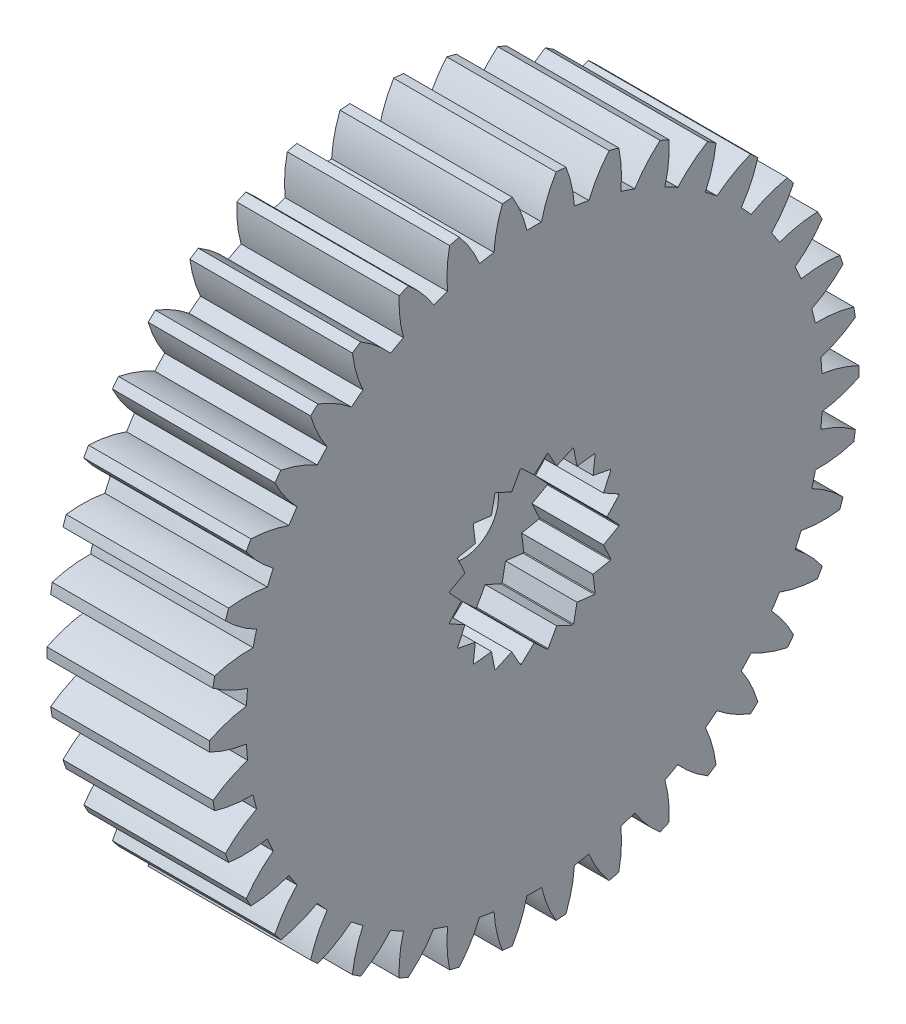
SolidWorks part; units mm, degrees
ref_plane "Plane1" through (0, 0, 0) normal (0, 0, 1) x (1, 0, 0)
ref_plane "Plane2" through (0, 0, 0) normal (0, 1, 0) x (1, 0, 0)
ref_plane "Plane3" through (0, 0, 0) normal (1, 0, 0) x (0, 0, -1)
sketch "HoldingSke" plane through (0, 0, 0) normal (0, 1, 0) x (1, 0, 0)
  line L0 (0, 0) -> (1.576, -1.2313)
  line L1 (-15, 0) -> (100, 0) construction
  line L2 (0, 0) -> (-2.1039, 2.3779)
  line L3 (0, 0) -> (-11.863, 4.5341)
  line L4 (0, 0) -> (6.8053, 5.3169)
  line L5 (0, 0) -> (-46.8476, -17.4728)
  line L6 (0, 0) -> (-4.1448, -2.7965)
  line L7 (-2.1039, 2.3779) -> (8.6586, 51.2059)
  line L8 (-76.2, 54.61) -> (-76.1, 54.61)
  line L9 (-71.009, 38.7566) -> (-53.1078, 45.2721)
  line L10 (-76.2, 71.12) -> (104.1128, 71.12)
  line L11 (0, 0) -> (-5, 0)
  line L12 (-76.2, 101.6) -> (-76.181, 101.6)
  line L13 (24.9733, 27.94) -> (52.9518, 28.4284)
  line L14 (24.9733, 27.94) -> (24.9743, 27.94)
  line L15 (24.9733, 27.94) -> (100.4006, 29.5858)
  line L16 (-63.627, -0.5) -> (-12.827, -0.5)
  circle A0 centre (0, 0) radius 0.4
  circle A1 centre (0, 0) radius 8.874
  circle A2 centre (0, 0) radius 37.5
  circle A3 centre (0, 0) radius 0.4
  dimension "MHD" = 17.748
  dimension "Hub_dia" = 75
  dimension "Bore" = 0.8
  dimension "MBD" = 0.8
  dimension "Num_teeth" = 38
  dimension "Pitch" = 2
  dimension "Overall_len" = 50
  dimension "Show_teeth" = 38
  dimension "Thickness" = 5
  dimension "OAL" = 50.0001
  dimension "T_dim" = 0.1
  dimension "Ap" = 20
  dimension "H" = 19.05
  dimension "Pitch_radius" = 180.3128
  dimension "Width" = 5
  dimension "Backlash" = 0.019
  dimension "Addendum_fac" = 1
  dimension "Dedendum_fac" = 1.25
  dimension "Clearance_fac" = 0.25
  dimension "Dedendum_add" = 0.001
  dimension "Module" = 0.5
sketch "BasProSke" plane through (0, 0, 0) normal (0, 1, 0) x (1, 0, 0)
  line L0 (-10, 0) -> (60, 0) construction
  line L1 (0, 0) -> (0, 10)
  line L2 (0, 0) -> (5, 0)
  line L3 (5, 0) -> (5, 10)
  line L4 (5, 10) -> (0, 10)
  dimension "Thickness" = 5
  dimension "Diameter" = 20
revolve "Base-Revolve" add sketch "BasProSke" angle 360 about L0
sketch "TooCutSke" plane through (0, 0, 0) normal (1, 0, 0) x (0, 0, -1)
  line L1 (0, 0) -> (0, 107) construction
  line L2 (0, 0) -> (-0.4258, 9.4905) construction
  line L3 (0, 0) -> (-1.5679, 18.9216) construction
  line L4 (-0.4258, 9.4905) -> (-0.7839, 9.4608) construction
  arc A0 (0.2256, 8.8711) -> (-0.2256, 8.8711) centre (0, 0) ccw
  arc A1 (0.6882, 10.0018) -> (-0.6882, 10.0018) centre (0, 0) ccw
  circle A2 centre (0, 0) radius 9.5 construction
  circle A3 centre (0, 0) radius 8.9271 construction
  arc A4 (-0.2256, 8.8711) -> (-0.6882, 10.0018) centre (-3.9283, 8.0163) ccw
  arc A5 (0.6882, 10.0018) -> (0.2256, 8.8711) centre (3.9283, 8.0163) ccw
  dimension "Root_dia" = 17.748
  dimension "Overcut_dia" = 20.0508
  dimension "Pitch_dia" = 19
  dimension "Base_dia" = 17.8542
  dimension "Flank_rad" = 3.8
  dimension "Half_ang" = 4.737
  dimension "Half_CT" = 0.3593
extrude "ToothCut" cut sketch "TooCutSke" along normal through all
fillet "Breaks" [suppressed] radius 0.01
fillet "RootFillets" [suppressed] radius 0.126
pattern_circular "TeethCuts" count 38 every 9.474 about axis through (-10, 0, 0) along (1, 0, 0) of "ToothCut", "RootFillets", "Breaks"
sketch "HubNeaOneSke" plane through (0, 0, 0) normal (-1, 0, 0) x (0, 0, 1)
  circle A0 centre (0, 0) radius 8.874
  dimension "Diameter" = 17.748
extrude "HubNearOne" [suppressed] add sketch "HubNeaOneSke" along normal blind 45.0001
sketch "HubNeaBotSke" plane through (0, 0, 0) normal (-1, 0, 0) x (0, 0, 1)
  circle A0 centre (0, 0) radius 8.874
  dimension "Diameter" = 17.748
extrude "HubNearBoth" [suppressed] add sketch "HubNeaBotSke" along normal blind 22.5
ref_plane "FarPln" through (5, 0, 0) normal (1, 0, 0) x (0, 0, -1)
sketch "HubFarSke" plane through (5, 0, 0) normal (1, 0, 0) x (0, 0, -1)
  circle A0 centre (0, 0) radius 8.874
  dimension "Diameter" = 17.748
extrude "HubFar" [suppressed] add sketch "HubFarSke" along normal blind 22.5
sketch "BorSke" plane through (0, 0, 0) normal (1, 0, 0) x (0, 0, -1)
  circle A0 centre (0, 0) radius 0.4
  dimension "Diameter" = 0.8
extrude "Bore" cut sketch "BorSke" along normal mid plane 100.0001
sketch "KeySke" plane through (0, 0, 0) normal (1, 0, 0) x (0, 0, -1)
  line L0 (-0.05, 0) -> (-0.05, 0.5)
  line L1 (-0.05, 0.5) -> (0.05, 0.5)
  line L2 (0.05, 0.5) -> (0.05, 0)
  line L3 (0, 0) -> (0, 34) construction
  line L4 (-0.05, 0) -> (0.05, 0)
  dimension "Offset" = 0.5
  dimension "Width" = 0.1
extrude "Keyway" [suppressed] cut sketch "KeySke" along normal mid plane 100.0001
pattern_circular "Keyway2" [suppressed] count 2 every 90 about axis through (-10, 0, 0) along (1, 0, 0)
sketch "Sketch2" plane through (5, 0, 0) normal (1, 0, 0) x (0, 0, -1)
  line L1 (-0.4307, 2.64) -> (0, 2.24)
  line L2 (0, 2.24) -> (0.4307, 2.64)
  line L4 (0.4307, 2.64) -> (-0.4307, 2.64)
  circle A1 centre (0, 0) radius 2.64
  point P11 (0, 2.64)
  dimension "D4" = 5.28
  dimension "D5" = 0.4
  dimension "D6" = 0.8613
sketch "Sketch3" plane through (5, 0, 0) normal (1, 0, 0) x (0, 0, -1)
  circle A0 centre (0, 0) radius 2.64 construction
  circle A1 centre (0, 0) radius 2.64
extrude "Cut-Extrude1" cut sketch "Sketch3" against normal blind 2.2
sketch "Sketch4" plane through (5, 0, 0) normal (1, 0, 0) x (0, 0, -1)
  line L0 (0, 2.24) -> (0.4307, 2.64) construction
  line L1 (-0.4307, 2.64) -> (0, 2.24) construction
  line L2 (0.4307, 2.64) -> (-0.4307, 2.64) construction
  line L3 (0, 2.24) -> (0.4307, 2.64)
  line L4 (-0.4307, 2.64) -> (0, 2.24)
  line L5 (0.4307, 2.64) -> (-0.4307, 2.64)
extrude "Boss-Extrude1" add sketch "Sketch4" against normal up to surface (2.2 mm away) up to face at (2.8, 0, -0.4)
pattern_circular "CirPattern1" count 20 over 360 about axis through (0, 0, 0) along (1, 0, 0) of "Boss-Extrude1"
sketch "Sketch5" plane through (0, 0, 0) normal (-1, 0, 0) x (0, 0, 1)
  circle A0 centre (0, 0) radius 2
  dimension "D1" = 4
extrude "Cut-Extrude2" cut sketch "Sketch5" against normal offset from surface (1.8 mm away) 1 up to face at (2.8, 0, 0)
sketch "Sketch6" plane through (1.8, 0, 0) normal (-1, 0, 0) x (0, 0, 1)
  circle A0 centre (0, 0) radius 1.1
  dimension "D1" = 2.2
extrude "Cut-Extrude3" cut sketch "Sketch6" against normal through all both and the other way through all
equation "' \"Module@HoldingSke\" = 6.35"
equation "' \"Num_teeth@HoldingSke\" = 12"
equation "' \"Ap@HoldingSke\" =  20"
equation "' \"Ap@HoldingSke\" = 20"
equation "' \"Width@HoldingSke\" = 0.5 * 25.4"
equation "' \"Hub_dia@HoldingSke\"= 1 * 25.4"
equation "' \"Hub_dia@HoldingSke\" = 1 * 25.4"
equation "' \"Overall_len@HoldingSke\" = 1.0 * 25.4"
equation "' \"Bore@HoldingSke\" = 0.75 * 25.4"
equation "' \"T_dim@HoldingSke\" = 0.1 * 25.4"
equation "' \"Width@KeySke\" = 0.25 * 25.4"
equation "' \"Show_teeth@HoldingSke\" = 13"
equation "' \"Backlash@HoldingSke\" = 0.009 * 25.4"
equation "' \"Addendum_fac@HoldingSke\" = 1.0"
equation "' \"Dedendum_fac@HoldingSke\" = 1.25"
equation "' \"Dedendum_add@HoldingSke\" = 0.00005 * 25.4"
equation "' \"Clearance_fac@HoldingSke\" = 0.25"
equation "\"Pitch@HoldingSke\" = 1 / \"Module@HoldingSke\""
equation "\"Overcut_dia@TooCutSke\" = (\"Num_teeth@HoldingSke\" + 2 * \"Addendum_fac@HoldingSke\") / \"Pitch@HoldingSke\" + 0.002 * 25.4"
equation "\"Pitch_dia@TooCutSke\" = \"Num_teeth@HoldingSke\" / \"Pitch@HoldingSke\""
equation "\"Base_dia@TooCutSke\" = \"Num_teeth@HoldingSke\" / \"Pitch@HoldingSke\" * cos((\"Ap@HoldingSke\"  * 3.14159265 / 180))"
equation "\"Root_dia@TooCutSke\" = (\"Num_teeth@HoldingSke\" + 2) / \"Pitch@HoldingSke\" - 2 * (\"Addendum_fac@HoldingSke\" + \"Dedendum_fac@HoldingSke\") / \"Pitch@HoldingSke\" - \"Dedendum_add@HoldingSke\" * 2"
equation "\"Half_ang@TooCutSke\" = 180 / \"Num_teeth@HoldingSke\""
equation "\"Half_CT@TooCutSke\" = \"Num_teeth@HoldingSke\" / \"Pitch@HoldingSke\" * sin((3.14159265 / 2 / \"Num_teeth@HoldingSke\")) / 2 - 7 * \"Backlash@HoldingSke\" / 4"
equation "\"Flank_rad@TooCutSke\" = \"Num_teeth@HoldingSke\" / \"Pitch@HoldingSke\" / 5"
equation "\"Radius@RootFillets\" = \"Clearance_fac@HoldingSke\" / \"Pitch@HoldingSke\" + \"Dedendum_add@HoldingSke\""
equation "\"Break_rad@Breaks\" = 0.02 / \"Pitch@HoldingSke\""
equation "\"Thickness@HoldingSke\" = \"Width@HoldingSke\""
equation "\"OAL@HoldingSke\" = \"Thickness@HoldingSke\""
equation "\"MHD@HoldingSke\" = (\"Num_teeth@HoldingSke\" + 2) / \"Pitch@HoldingSke\" - 2 * (\"Addendum_fac@HoldingSke\" + \"Dedendum_fac@HoldingSke\")  / \"Pitch@HoldingSke\" - \"Dedendum_add@HoldingSke\" * 2"
equation "\"MBD@HoldingSke\" = (\"Num_teeth@HoldingSke\" + 2) / \"Pitch@HoldingSke\" - 2 * (\"Addendum_fac@HoldingSke\" + \"Dedendum_fac@HoldingSke\")  / \"Pitch@HoldingSke\" - \"Dedendum_add@HoldingSke\" * 2 - 0.002 * 25.4"
equation "\"MHD@HoldingSke\" = ((sgn( \"MHD@HoldingSke\" - \"Hub_dia@HoldingSke\" )-1)*( \"MHD@HoldingSke\" - \"Hub_dia@HoldingSke\" ))/-2+ \"Hub_dia@HoldingSke\""
equation "\"MBD@HoldingSke\" = ((sgn( \"MBD@HoldingSke\" - \"Bore@HoldingSke\" )-1)*( \"MBD@HoldingSke\" - \"Bore@HoldingSke\" ))/-2+ \"Bore@HoldingSke\""
equation "\"OAL@HoldingSke\" = ((sgn( \"OAL@HoldingSke\" - \"Overall_len@HoldingSke\" )+1)*( \"OAL@HoldingSke\" - \"Overall_len@HoldingSke\" ))/2 + \"Overall_len@HoldingSke\" + 0.000002 * 25.4"
equation "\"Num_teeth@TeethCuts\" = int( \"Show_teeth@HoldingSke\" ) + 1"
equation "\"Num_teeth@TeethCuts\" = ((sgn( \"Num_teeth@TeethCuts\" - \"Num_teeth@HoldingSke\" )-1)*( \"Num_teeth@TeethCuts\" - \"Num_teeth@HoldingSke\" ))/-2+ \"Num_teeth@HoldingSke\""
equation "\"Num_teeth@TeethCuts\" = ((sgn( \"Num_teeth@TeethCuts\" - 2.0)+1)*( \"Num_teeth@TeethCuts\" - 2.0))/2 +2.0"
equation "\"Angle@TeethCuts\" = 360.0 / \"Num_teeth@HoldingSke\""
equation "\"Diameter@BasProSke\" = (\"Num_teeth@HoldingSke\" + 2 * \"Addendum_fac@HoldingSke\") / \"Pitch@HoldingSke\""
equation "\"Thickness@BasProSke\"  = \"Thickness@HoldingSke\""
equation "' \"Fillet_rad@BasProSke\" =  \"Thickness@HoldingSke\" * 0.05"
equation "' \"Fillet_rad@BasProSke\" = \"Thickness@HoldingSke\" * 0.05"
equation "\"MHD@HoldingSke\" = ((sgn( \"MHD@HoldingSke\" - \"Root_dia@TooCutSke\" )-1)*( \"MHD@HoldingSke\" - \"Root_dia@TooCutSke\" ))/-2+ \"Root_dia@TooCutSke\""
equation "\"Diameter@HubNeaOneSke\" = \"MHD@HoldingSke\""
equation "\"Length@HubNearOne\" = \"OAL@HoldingSke\" - \"Thickness@BasProSke\""
equation "\"Diameter@HubNeaBotSke\" = \"MHD@HoldingSke\""
equation "\"Length@HubNearBoth\" = ( \"OAL@HoldingSke\" - \"Thickness@BasProSke\" ) / 2.0"
equation "\"Thickness@FarPln\" = \"Thickness@BasProSke\""
equation "\"Diameter@HubFarSke\" = \"MHD@HoldingSke\""
equation "\"Length@HubFar\" = ( \"OAL@HoldingSke\" - \"Thickness@BasProSke\" ) / 2.0"
equation "\"Diameter@BorSke\" = \"MBD@HoldingSke\""
equation "\"D1@Bore\" = \"OAL@HoldingSke\" * 2.0"
equation "\"D1@Keyway\" = \"OAL@HoldingSke\" * 2.0"
equation "\"Offset@KeySke\" = \"T_dim@HoldingSke\" + \"MBD@HoldingSke\" / 2.0"
